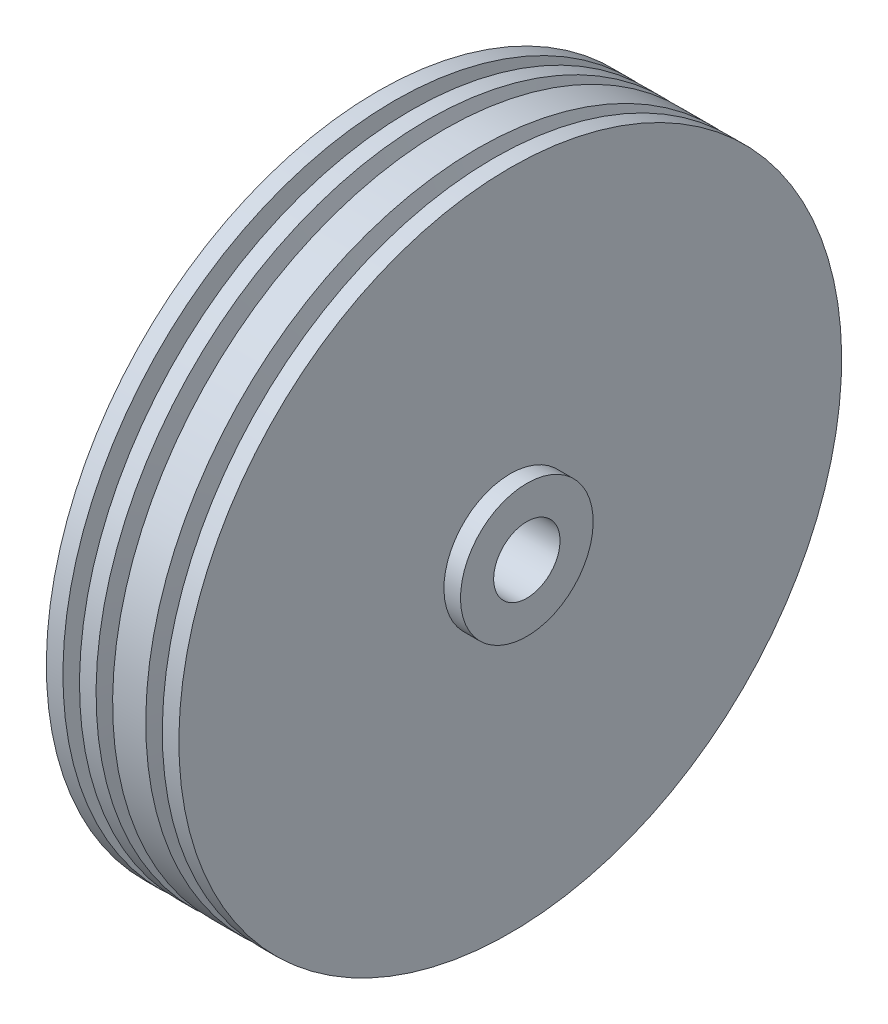
SolidWorks part; units mm, degrees
ref_plane "Alzado" through (0, 0, 0) normal (0, 0, 1) x (1, 0, 0)
ref_plane "Planta" through (0, 0, 0) normal (0, 1, 0) x (1, 0, 0)
ref_plane "Vista lateral" through (0, 0, 0) normal (1, 0, 0) x (0, 0, -1)
sketch "Croquis1" plane through (0, 0, 0) normal (0, 0, 1) x (1, 0, 0)
  line L0 (0, 0) -> (68.9056, 0) construction
  line L1 (68.9056, 0) -> (-115.1801, 0) construction
  line L2 (-15.2242, 10.0164) -> (-35.2242, 10.0164)
  line L3 (-35.2242, 10.0164) -> (-35.2242, 20.0164)
  line L4 (-35.2242, 20.0164) -> (-30.2242, 20.0164)
  line L5 (-30.2242, 20.0164) -> (-30.2242, 80.0164)
  line L6 (-30.2242, 80.0164) -> (-50.2242, 80.0164)
  line L8 (-50.2242, 100.0164) -> (-45.2242, 100.0164)
  line L9 (-15.2242, 10.0164) -> (-15.2242, 20.0164)
  line L10 (-15.2242, 20.0164) -> (-20.2242, 20.0164)
  line L11 (-20.2242, 20.0164) -> (-20.2242, 80.0164)
  line L12 (-20.2242, 80.0164) -> (-20.2242, 100.0164)
  line L13 (-20.2242, 100.0164) -> (-25.2242, 100.0164)
  line L17 (-30.2242, 100.0164) -> (-40.2242, 100.0164)
  line L31 (-45.2242, 100.0164) -> (-42.7242, 90.0164)
  line L32 (-42.7242, 90.0164) -> (-40.2242, 100.0164)
  line L33 (-30.2242, 100.0164) -> (-27.7242, 90.0164)
  line L34 (-27.7242, 90.0164) -> (-25.2242, 100.0164)
  line L35 (-50.2242, 80.0164) -> (-60.2242, 80.0164)
  line L36 (-60.2242, 80.0164) -> (-60.2242, 100.0164)
  line L37 (-60.2242, 100.0164) -> (-55.2242, 100.0164)
  line L38 (-55.2242, 100.0164) -> (-55.2242, 90.0164)
  line L39 (-55.2242, 90.0164) -> (-50.2242, 90.0164)
  line L40 (-50.2242, 90.0164) -> (-50.2242, 100.0164)
revolve "Revolución2" add sketch "Croquis1" angle 360 about L1
